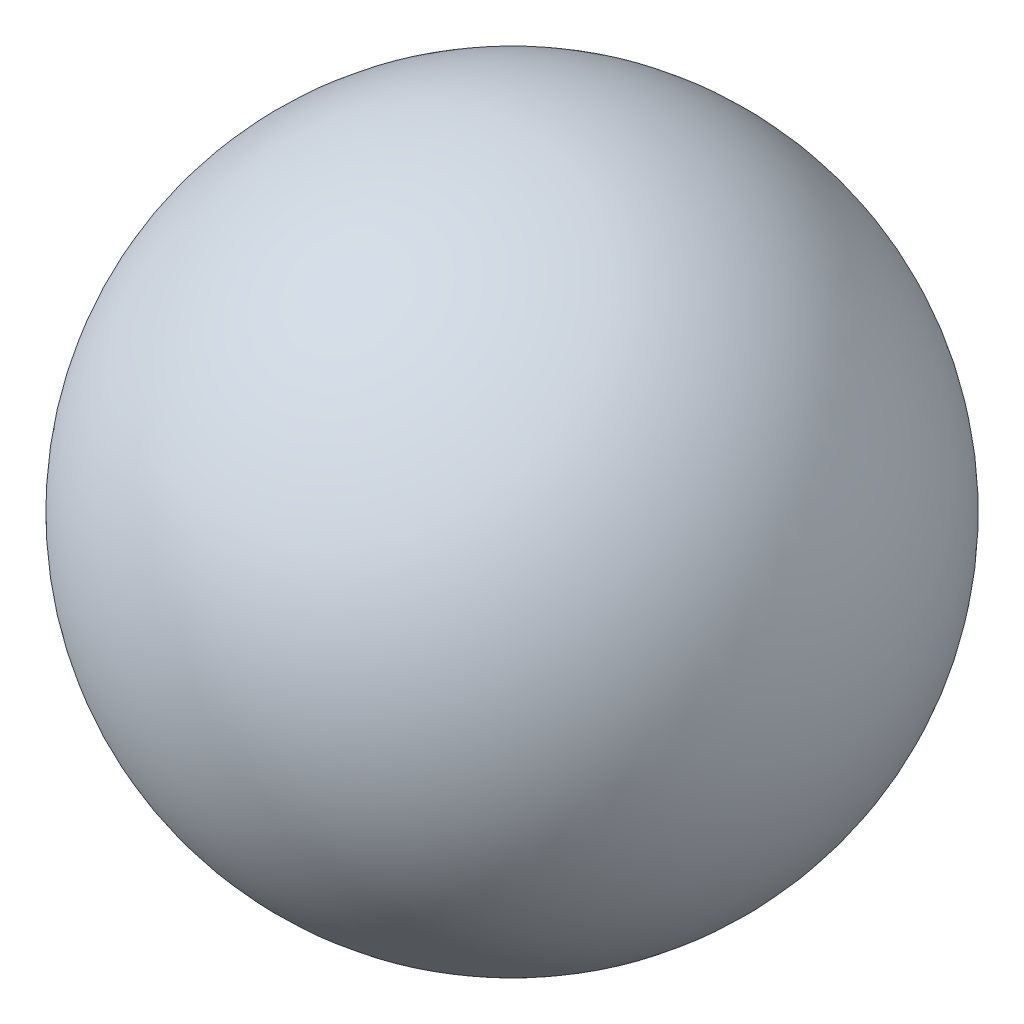
SolidWorks part; units mm, degrees
ref_plane "Front Plane" through (0, 0, 0) normal (0, 0, 1) x (1, 0, 0)
ref_plane "Top Plane" through (0, 0, 0) normal (0, 1, 0) x (1, 0, 0)
ref_plane "Right Plane" through (0, 0, 0) normal (1, 0, 0) x (0, 0, -1)
sketch "Sketch1" plane through (0, 0, 0) normal (0, 0, 1) x (1, 0, 0)
  line L0 (0, 53.3148) -> (0, -52.6327) construction
  line L1 (0, 20.32) -> (0, -20.32)
  arc A0 (0, 20.32) -> (0, -20.32) centre (0, 0) ccw
  dimension "D1" = 20.32
revolve "Revolve1" add sketch "Sketch1" angle 360 about L0
equation "\"D1@Sketch1\"=1.6/2"
